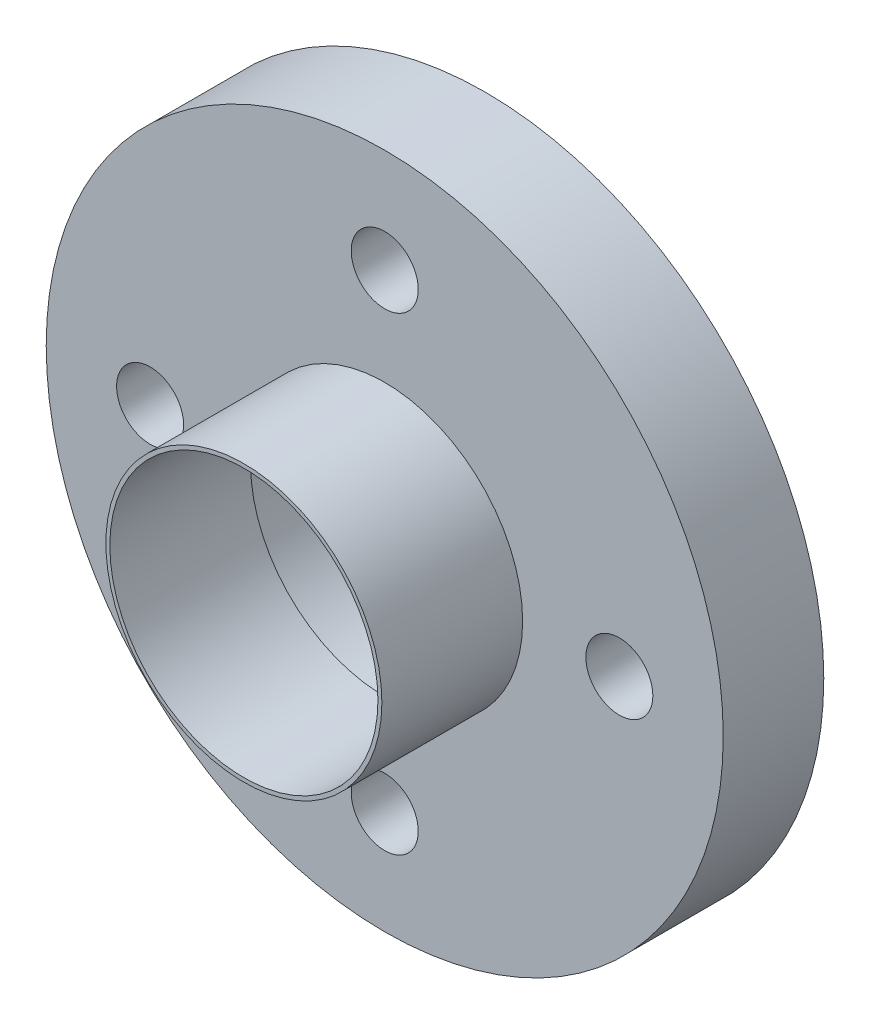
SolidWorks part; units mm, degrees
ref_plane "Ön Düzlem" through (0, 0, 0) normal (0, 0, 1) x (1, 0, 0)
ref_plane "Üst Düzlem" through (0, 0, 0) normal (0, 1, 0) x (1, 0, 0)
ref_plane "Sağ Düzlem" through (0, 0, 0) normal (1, 0, 0) x (0, 0, -1)
sketch "Çizim1" plane through (0, 0, 0) normal (0, 0, 1) x (1, 0, 0)
  circle A1 centre (-49.8251, -15.9756) radius 1
  circle A3 centre (-56.8251, -8.9756) radius 1
  circle A4 centre (-49.8251, -1.9756) radius 1
  circle A5 centre (-42.8251, -8.9756) radius 1
  circle A7 centre (-49.8251, -8.9756) radius 4.1
  arc A9 (-49.8251, 1.1244) -> (-49.8251, -19.0756) centre (-49.8251, -8.9756) ccw
  arc A10 (-49.8251, 1.1244) -> (-49.8251, -19.0756) centre (-49.8251, -8.9756) cw
  point P4 (-59.8251, 1.0244)
  point P9 (-59.8251, -18.9756)
  point P16 (-49.8251, -8.9756)
  dimension "D2" = 2
  dimension "D3" = 14
extrude "Yükseklik-Ekstrüzyon1" add sketch "Çizim1" along normal blind 3
sketch "Çizim4" plane through (0, 0, 3) normal (0, 0, 1) x (1, 0, 0)
  circle A0 centre (-49.8273, -8.9928) radius 4.1173
  circle A1 centre (-49.8273, -8.9928) radius 4
  dimension "D1" = 8
extrude "Yükseklik-Ekstrüzyon4" add sketch "Çizim4" along normal blind 4.2 separate body
